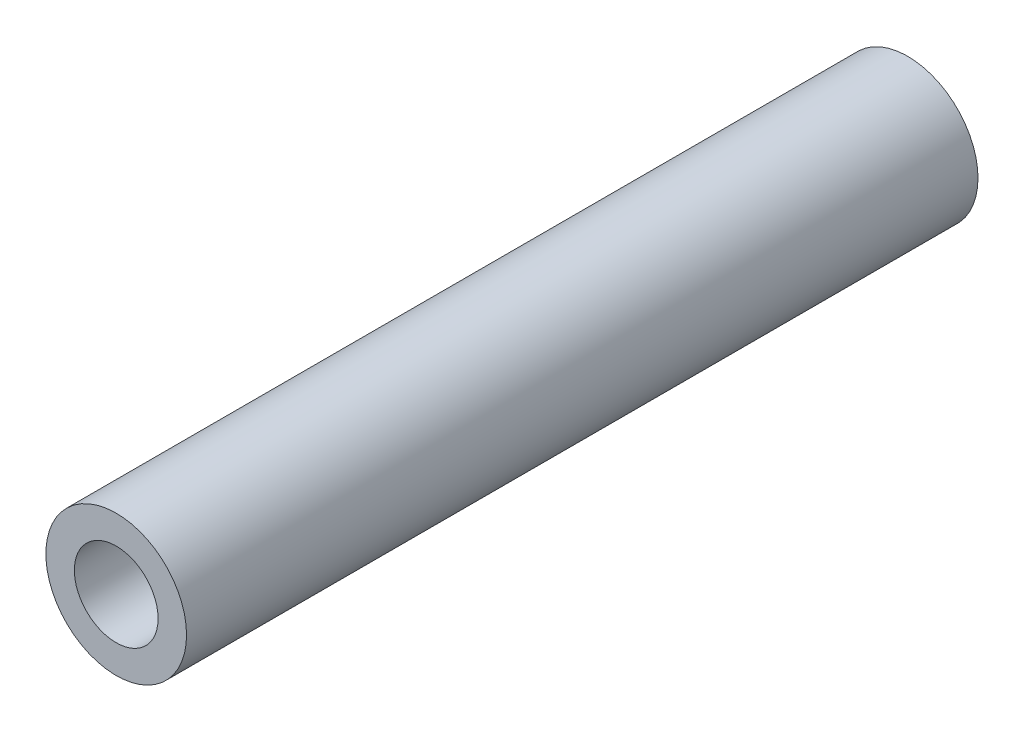
SolidWorks part; units mm, degrees
ref_plane "Front Plane" through (0, 0, 0) normal (0, 0, 1) x (1, 0, 0)
ref_plane "Top Plane" through (0, 0, 0) normal (0, 1, 0) x (1, 0, 0)
ref_plane "Right Plane" through (0, 0, 0) normal (1, 0, 0) x (0, 0, -1)
sketch "Sketch1" plane through (0, 0, 0) normal (0, 0, 1) x (1, 0, 0)
  circle A0 centre (0, 0) radius 6.35
  circle A1 centre (0, 0) radius 10.665
  dimension "D1" = 12.7
  dimension "D2" = 21.33
extrude "Boss-Extrude1" add sketch "Sketch1" along normal blind 120
sketch "Croquis1" plane through (0, 0, 0) normal (0, 0, 1) x (1, 0, 0)
  line L0 (0, 0) -> (49.8274, 0)
  line L1 (0, 0) -> (0, 32.4055)
pattern_linear "MatrizL1" [suppressed] count 30 spacing 21.33 along (1, 0, 0) count 30 spacing 21.33 along (0, 1, 0)
